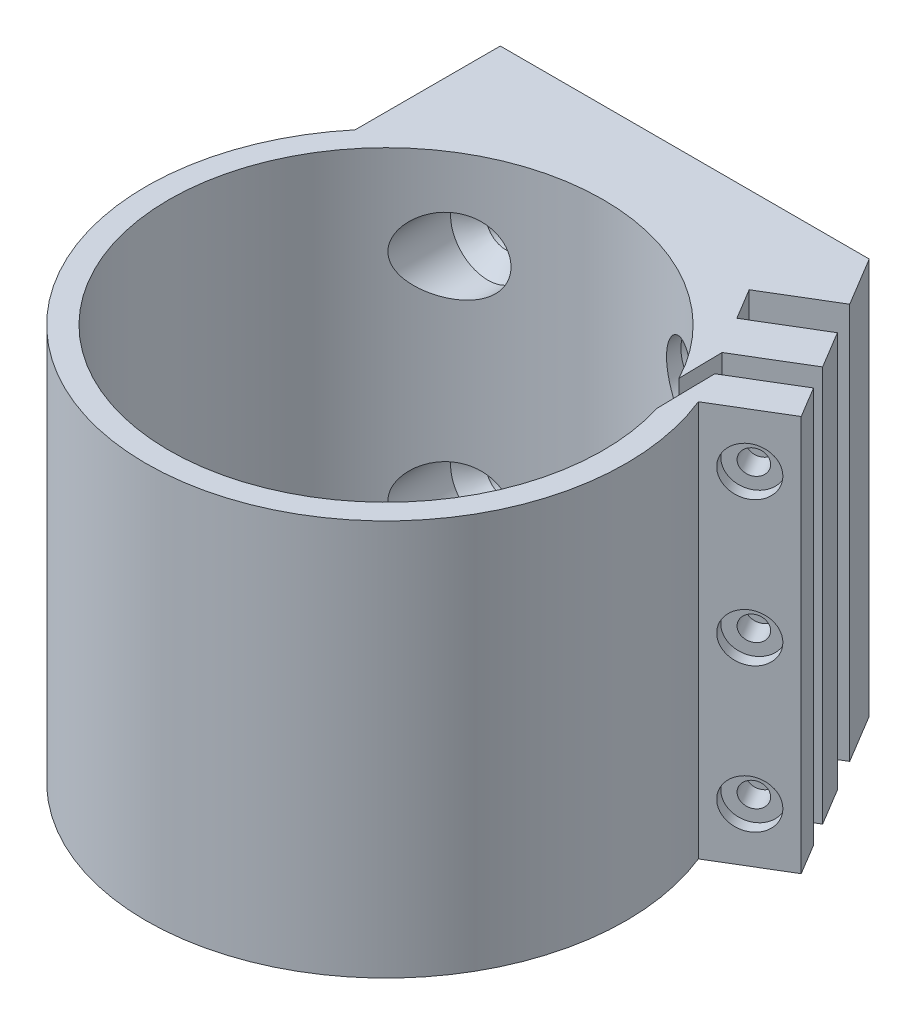
SolidWorks part; units mm, degrees
ref_plane "Front Plane" through (0, 0, 0) normal (0, 0, 1) x (1, 0, 0)
ref_plane "Top Plane" through (0, 0, 0) normal (0, 1, 0) x (1, 0, 0)
ref_plane "Right Plane" through (0, 0, 0) normal (1, 0, 0) x (0, 0, -1)
sketch "Sketch1" plane through (0, 0, 0) normal (0, 1, 0) x (1, 0, 0)
  line L0 (-25.625, 21.3248) -> (-25.625, 41.4953)
  line L5 (-25.625, 41.4953) -> (-20.625, 41.4953)
  line L6 (-20.625, 41.4953) -> (-20.625, 35.3375)
  line L7 (-20.625, 35.3375) -> (20.625, 35.3375)
  line L8 (20.625, 35.3375) -> (20.625, 41.4953)
  line L9 (20.625, 41.4953) -> (25.625, 41.4953)
  line L10 (25.625, 41.4953) -> (25.625, 21.3248) construction
  line L11 (26.6477, 20.0322) -> (26.7543, 13.9279)
  line L12 (28.7017, 16.9589) -> (28.8437, 8.8214)
  line L14 (26.6477, 20.0322) -> (35.3717, 25.2741)
  line L15 (28.7017, 16.9589) -> (37.2733, 22.1093)
  line L16 (37.2733, 22.1093) -> (39.8485, 17.8234)
  line L17 (39.8485, 17.8234) -> (30.9216, 12.4596)
  line L18 (35.3717, 25.2741) -> (25.625, 41.4953)
  line L19 (32.2815, 30.4171) -> (23.5575, 25.1752)
  line L20 (23.5575, 25.1752) -> (20.9823, 29.461)
  line L21 (20.9823, 29.461) -> (29.7063, 34.7029)
  line L22 (23.5575, 25.1752) -> (26.6477, 20.0322) construction
  arc A0 (-25.625, 21.3248) -> (30.9216, 12.4596) centre (0, 0) ccw
  arc A1 (26.7543, 13.9279) -> (28.8437, 8.8214) centre (0, 0) ccw
  arc A2 (26.6477, 20.0322) -> (25.625, 21.3248) centre (0, 0) ccw construction
  arc A3 (30.9216, 12.4596) -> (28.7017, 16.9589) centre (0, 0) ccw construction
  point P9 (0, 35.3375)
  point P13 (0, 33.3375)
  dimension "D2" = 3.175
  dimension "D4" = 30.1625
  dimension "D3" = 41.25
  dimension "D5" = 5
  dimension "D6" = 2
  dimension "D7" = 1
  dimension "D8" = 2
  dimension "D9" = 1
  dimension "D10" = 120
  dimension "D11" = 10
  dimension "D12" = 5
  dimension "D13" = 6
  dimension "D14" = 5
extrude "Boss-Extrude1" add sketch "Sketch1" along normal mid plane 55 contours A1 L11 L14 L18 L19 L20 L21 L9 L8 L7 L6 L5 L0 A0 L17 L16 L15 L12
hole_wizard "CBORE for M3 SBHCS1" positions "Sketch2" profile "Sketch3" counterbore size "M3" standard "ANSI Metric"
sketch "Sketch2" plane through (2.7018, 0, 4.4966) normal (0.515, 0, 0.8572) x (0.8572, 0, -0.515)
  line L0 (32.9222, 27.5) -> (43.3366, 27.5) construction
  line L1 (43.3366, 27.5) -> (43.3366, -27.5) construction
  point P0 (38.1294, 20)
  point P2 (38.1294, 0)
  point P4 (38.1294, -20)
  point P16 (38.1294, 27.5)
  dimension "D1" = 20
  dimension "D2" = 20
sketch "Sketch3" plane through (35.3851, 20, -15.1415) normal (0, 1, 0) x (0.8572, 0, -0.515)
  line L0 (0, 0) -> (0, 21.0215)
  line L1 (0, 21.0215) -> (1.7, 20)
  line L2 (1.7, 20) -> (1.7, 1.65)
  line L3 (1.7, 1.65) -> (3.35, 1.65)
  line L4 (3.35, 1.65) -> (3.35, 0)
  line L5 (3.35, 0) -> (0, 0)
  line L10 (0, 21.0215) -> (-1.7, 20) construction
  line L11 (0, -6.35) -> (0, 107.95) construction
  dimension "Hole Dia." = 3.4
  dimension "Hole Depth" = 20
  dimension "C'Bore Dia." = 6.7
  dimension "C'Bore Depth" = 1.65
  dimension "Drill Angle" = 118
sketch "Sketch4" plane through (0, 27.5, 0) normal (0, -1, 0) x (1, 0, 0)
  line L1 (-20.625, -35.3375) -> (20.625, -35.3375)
  line L2 (-20.625, -35.3375) -> (-20.625, -41.4953)
  line L3 (-20.625, -41.4953) -> (20.625, -41.4953)
  line L4 (20.625, -35.3375) -> (20.625, -41.4953)
extrude "Boss-Extrude2" add sketch "Sketch4" along normal blind 4.5
ref_plane "Plane1" through (0, 0, -30.1625) normal (0, 0, 1) x (1, 0, 0)
sketch "Sketch6" plane through (0, 0, -30.1625) normal (0, 0, 1) x (1, 0, 0)
  line L1 (16, -15) -> (-16, -15) construction
  line L2 (16, -15) -> (16, 15) construction
  line L3 (16, 15) -> (-16, 15) construction
  line L4 (-16, -15) -> (-16, 15) construction
  line L5 (16, -15) -> (-16, 15) construction
  line L6 (16, 15) -> (-16, -15) construction
  point P0 (0, 0)
  dimension "D1" = 32
  dimension "D2" = 30
hole_wizard "CSK for M5 Flat Head Machine Screw1" positions "Sketch10" profile "Sketch12" countersink size "M5" standard "ANSI Metric"
sketch "Sketch10" plane through (0, 0, -30.1625) normal (0, 0, 1) x (1, 0, 0)
  point P0 (-16, 15)
  point P3 (16, 15)
  point P6 (16, -15)
  point P9 (-16, -15)
sketch "Sketch12" plane through (-16, 15, -30.1625) normal (1, 0, 0) x (0, -1, 0)
  line L0 (0, 0) -> (0, 11.3328)
  line L1 (0, 11.3328) -> (2.75, 11.3328)
  line L2 (2.75, 11.3328) -> (2.75, 2.45)
  line L3 (2.75, 2.45) -> (5.2, 0)
  line L5 (5.2, 0) -> (0, 0)
  line L6 (-2.75, 2.45) -> (-5.2, 0) construction
  line L11 (0, -6.35) -> (0, 107.95) construction
  dimension "Thru Hole Dia." = 5.5
  dimension "Thru Hole Depth" = 11.3328
  dimension "Near C'Sink Dia." = 10.4
  dimension "Near C'Sink Angle" = 90
sketch "Sketch13" plane through (0, 0, -30.1625) normal (0, 0, 1) x (1, 0, 0)
  circle A0 centre (-16, -15) radius 5.2 construction
  circle A1 centre (16, -15) radius 5.2 construction
  circle A2 centre (16, 15) radius 5.2 construction
  circle A3 centre (-16, 15) radius 5.2 construction
  circle A4 centre (-16, -15) radius 5.2
  circle A5 centre (16, -15) radius 5.2
  circle A6 centre (16, 15) radius 5.2
  circle A7 centre (-16, 15) radius 5.2
extrude "Cut-Extrude1" cut sketch "Sketch13" along normal up to next
